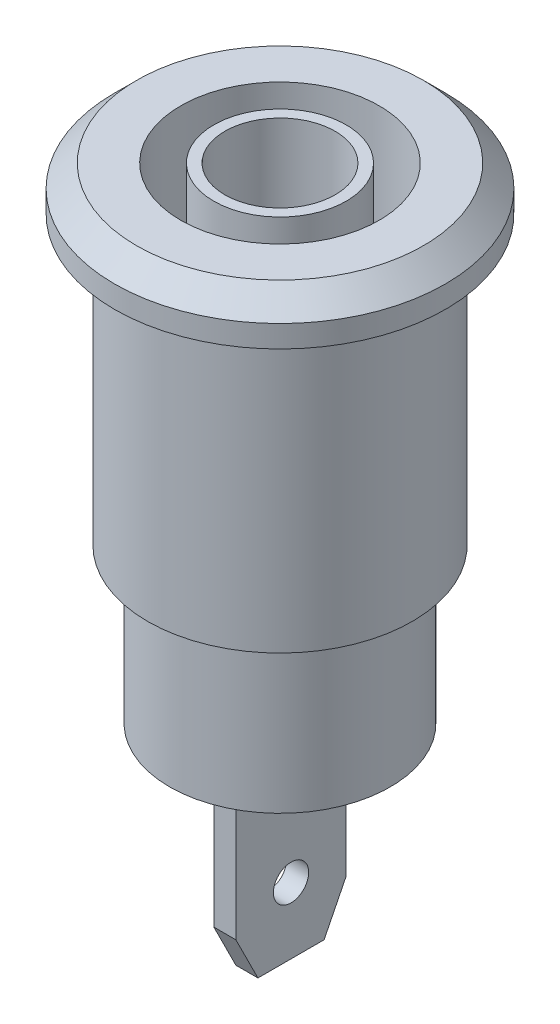
SolidWorks part; units mm, degrees
material "PW80:Mi:0:30:C1:0:1:2:Re:16:"
ref_plane "Plan1" through (0, 0, 0) normal (0, 0, 1) x (1, 0, 0)
ref_plane "Plan2" through (0, 0, 0) normal (0, 1, 0) x (1, 0, 0)
ref_plane "Plan3" through (0, 0, 0) normal (1, 0, 0) x (0, 0, -1)
sketch "Esquisse1" plane through (0, 0, 0) normal (1, 0, 0) x (0, 0, -1)
  line L0 (0, 0) -> (7.5, 0)
  line L1 (7.5, 0) -> (7.5, -2)
  line L2 (7.5, -2) -> (6, -2)
  line L3 (6, -2) -> (6, -15)
  line L4 (6, -15) -> (5, -15)
  line L5 (5, -15) -> (5, -22)
  line L6 (5, -22) -> (0, -22)
  line L7 (0, -22) -> (0, 0)
  line L8 (0, 10) -> (0, -30) construction
revolve "Base-Révolution" add sketch "Esquisse1" angle 360 about L8
chamfer "Chanfrein1" distance 1 angle 45
sketch "Esquisse2" plane through (0, 0, 0) normal (0, 1, 0) x (-1, 0, 0)
  circle A0 centre (0, 0) radius 4.5
extrude "Enlèv. mat.-Extru.1" cut sketch "Esquisse2" against normal blind 12
sketch "Esquisse3" plane through (0, -12, 0) normal (0, 1, 0) x (-1, 0, 0)
  circle A0 centre (0, 0) radius 3
extrude "Boss.-Extru.1" add sketch "Esquisse3" along normal blind 12
sketch "Esquisse4" plane through (0, 0, 0) normal (0, 1, 0) x (-1, 0, 0)
  circle A0 centre (0, 0) radius 2.5
extrude "Enlèv. mat.-Extru.2" cut sketch "Esquisse4" against normal blind 12
ref_plane "Plan4" through (0.5, 0, 0) normal (1, 0, 0) x (0, 0, -1)
sketch "Esquisse5" plane through (0.5, 0, 0) normal (1, 0, 0) x (0, 0, -1)
  line L0 (-5, -22) -> (5, -22) construction
  line L1 (-2.5, -22) -> (2.5, -22)
  line L2 (-2.5, -22) -> (-2.5, -31)
  line L3 (-2.5, -31) -> (2.5, -31)
  line L4 (2.5, -22) -> (2.5, -31)
extrude "Boss.-Extru.2" add sketch "Esquisse5" against normal blind 1
sketch "Esquisse6" plane through (0.5, 0, 0) normal (1, 0, 0) x (0, 0, -1)
  line L0 (-2.5, -29) -> (-1.5, -31)
  line L1 (-2.5, -22) -> (-2.5, -31) construction
  line L2 (-2.5, -31) -> (2.5, -31) construction
  line L3 (-1.5, -31) -> (-2.5, -31)
  line L4 (-2.5, -31) -> (-2.5, -29)
extrude "Enlèv. mat.-Extru.3" cut sketch "Esquisse6" against normal blind 1
sketch "Esquisse7" plane through (0.5, 0, 0) normal (1, 0, 0) x (0, 0, -1)
  line L0 (2.5, -31) -> (2.5, -29)
  line L1 (2.5, -31) -> (2.5, -22) construction
  line L2 (2.5, -29) -> (1.5, -31)
  line L3 (-1.5, -31) -> (2.5, -31) construction
  line L4 (1.5, -31) -> (2.5, -31)
extrude "Enlèv. mat.-Extru.4" cut sketch "Esquisse7" against normal blind 1
sketch "Esquisse8" plane through (0.5, 0, 0) normal (1, 0, 0) x (0, 0, -1)
  circle A0 centre (0, -28) radius 0.8
extrude "Enlèv. mat.-Extru.5" cut sketch "Esquisse8" against normal blind 1
